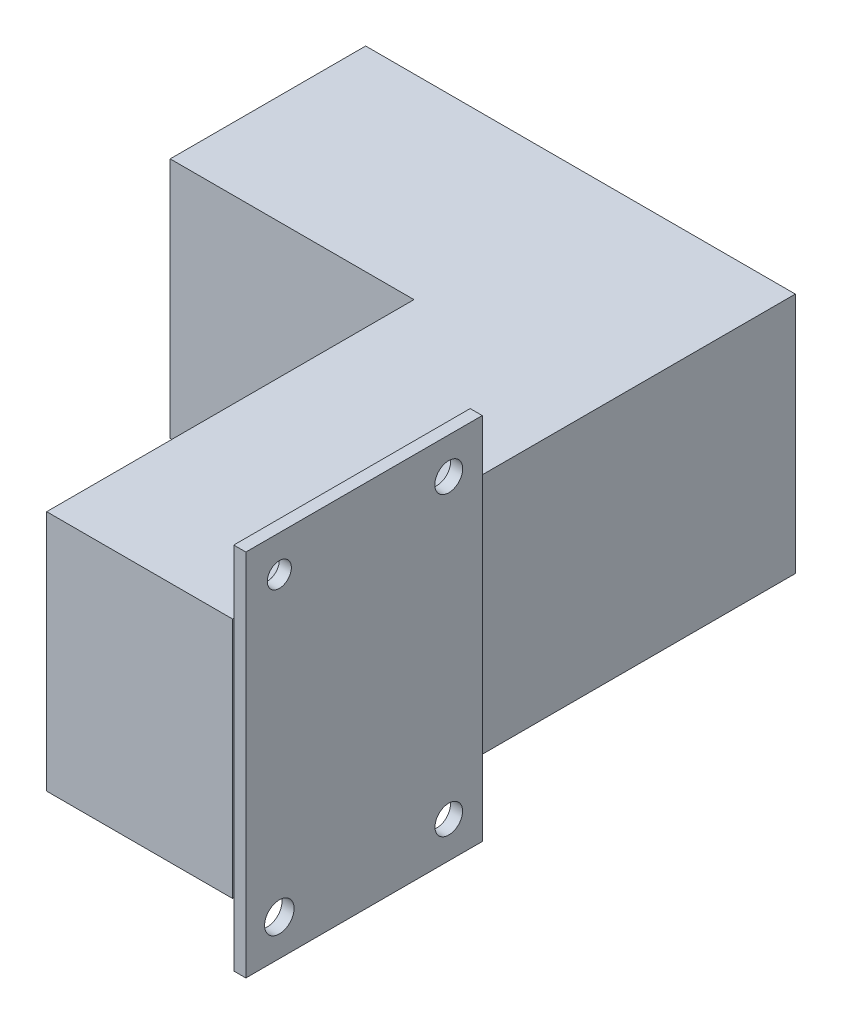
SolidWorks part; units mm, degrees
ref_plane "前视基准面" through (0, 0, 0) normal (0, 0, 1) x (1, 0, 0)
ref_plane "上视基准面" through (0, 0, 0) normal (0, 1, 0) x (1, 0, 0)
ref_plane "右视基准面" through (0, 0, 0) normal (1, 0, 0) x (0, 0, -1)
sketch "草图1" plane through (0, 0, 0) normal (0, 0, 1) x (1, 0, 0)
  line L1 (-35.5, -20) -> (35.5, -20)
  line L2 (-35.5, -20) -> (-35.5, 20)
  line L3 (-35.5, 20) -> (35.5, 20)
  line L4 (35.5, -20) -> (35.5, 20)
  line L5 (-35.5, -20) -> (35.5, 20) construction
  line L6 (-35.5, 20) -> (35.5, -20) construction
  point P0 (0, 0)
  dimension "D1" = 71
  dimension "D2" = 40
extrude "凸台-拉伸1" add sketch "草图1" along normal blind 93
sketch "草图2" plane through (0, 0, 0) normal (1, 0, 0) x (0, 0, -1)
  line L1 (-87.2668, -24.5) -> (-59.2668, -24.5) construction
  line L2 (-87.2668, -24.5) -> (-87.2668, 24.5) construction
  line L3 (-87.2668, 24.5) -> (-59.2668, 24.5) construction
  line L4 (-59.2668, -24.5) -> (-59.2668, 24.5) construction
  line L5 (-87.2668, -24.5) -> (-59.2668, 24.5) construction
  line L6 (-87.2668, 24.5) -> (-59.2668, -24.5) construction
  line L7 (-92.7987, -30.4803) -> (-53.7348, -30.4803)
  line L8 (-92.7987, -30.4803) -> (-92.7987, 30.4803)
  line L9 (-92.7987, 30.4803) -> (-53.7348, 30.4803)
  line L10 (-53.7348, -30.4803) -> (-53.7348, 30.4803)
  line L11 (-92.7987, -30.4803) -> (-53.7348, 30.4803) construction
  line L12 (-92.7987, 30.4803) -> (-53.7348, -30.4803) construction
  circle A0 centre (-87.2668, 24.5) radius 1.9868
  circle A1 centre (-59.2668, 24.5) radius 2.3032
  circle A2 centre (-87.2668, -24.5) radius 2.4356
  circle A3 centre (-59.2668, -24.5) radius 2.2796
  point P0 (-73.2668, 0)
  point P9 (-73.2668, 0)
  dimension "D1" = 49
  dimension "D2" = 28
extrude "凸台-拉伸2" add sketch "草图2" along normal blind 2 from surface at 35.5 starting at face at (35.5, 0, 46.5)
sketch "草图3" plane through (0, 20, 0) normal (0, 1, 0) x (1, 0, 0)
  line L0 (4.7865, -93) -> (4.7865, -32.3049)
  line L1 (35.5, -93) -> (-35.5, -93) construction
  line L2 (4.7865, -32.3049) -> (-35.5, -32.3049)
  line L3 (-35.5, -93) -> (-35.5, 0) construction
  line L4 (-35.5, -32.3049) -> (-48.137, -34.9162)
  line L5 (-48.137, -34.9162) -> (-56.3193, -69.4732)
  line L6 (-56.3193, -69.4732) -> (-51.9355, -90.6877)
  line L7 (-51.9355, -90.6877) -> (-39.6936, -97.3277)
  line L8 (-39.6936, -97.3277) -> (4.7865, -93)
extrude "切除-拉伸1" cut sketch "草图3" against normal blind 67
